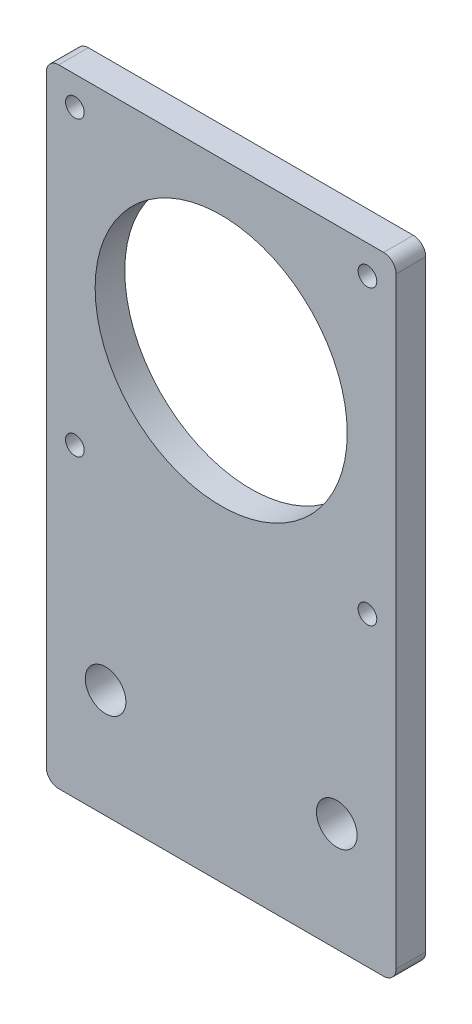
SolidWorks part; units mm, degrees
material "6061 Alloy"
ref_plane "Front Plane" through (0, 0, 0) normal (0, 0, 1) x (1, 0, 0)
ref_plane "Top Plane" through (0, 0, 0) normal (0, 1, 0) x (1, 0, 0)
ref_plane "Right Plane" through (0, 0, 0) normal (1, 0, 0) x (0, 0, -1)
sketch "Sketch1" plane through (0, 0, 0) normal (0, 0, 1) x (1, 0, 0)
  line L1 (-28.1, 50.3625) -> (28.1, 50.3625)
  line L2 (-28.1, 50.3625) -> (-28.1, -50.3625)
  line L3 (-28.1, -50.3625) -> (28.1, -50.3625)
  line L4 (28.1, 50.3625) -> (28.1, -50.3625)
  line L5 (-28.1, 50.3625) -> (28.1, -50.3625) construction
  line L6 (-28.1, -50.3625) -> (28.1, 50.3625) construction
  point P0 (0, 0)
  dimension "D1" = 100.725
  dimension "D2" = 56.2
extrude "Boss-Extrude1" add sketch "Sketch1" along normal mid plane 4.7625
sketch "Sketch2" plane through (0, 0, 2.3813) normal (0, 0, 1) x (1, 0, 0)
  line L0 (28.1, -50.3625) -> (28.1, 50.3625) construction
  line L2 (28.1, 50.3625) -> (-28.1, 50.3625) construction
  line L3 (-28.1, 50.3625) -> (-28.1, -50.3625) construction
  line L4 (-28.1, -50.3625) -> (28.1, -50.3625) construction
  circle A0 centre (0, 22.2625) radius 20.25
  circle A1 centre (-23.5, 45.7625) radius 1.5
  circle A2 centre (23.5, 45.7625) radius 1.5
  circle A3 centre (-23.5, -1.2375) radius 1.5
  circle A4 centre (23.5, -1.2375) radius 1.5
  circle A5 centre (-18.575, -32.9) radius 3.2639
  circle A6 centre (18.575, -32.9) radius 3.2639
  point P12 (0, 0)
  point P19 (0, 0)
  dimension "D1" = 3
  dimension "D2" = 40.5
  dimension "D3" = 6.5278
  dimension "D6" = 47
  dimension "D4" = 4.6
  dimension "D5" = 47
  dimension "D7" = 4.6
  dimension "D8" = 28.1
  dimension "D9" = 9.525
  dimension "D10" = 9.525
  dimension "D11" = 17.4625
extrude "Cut-Extrude1" cut sketch "Sketch2" against normal through all
fillet "Fillet1" radius 2 4 edges at (28.1, -50.3625, 0) (-28.1, -50.3625, 0) (-28.1, 50.3625, 0) (28.1, 50.3625, 0)
